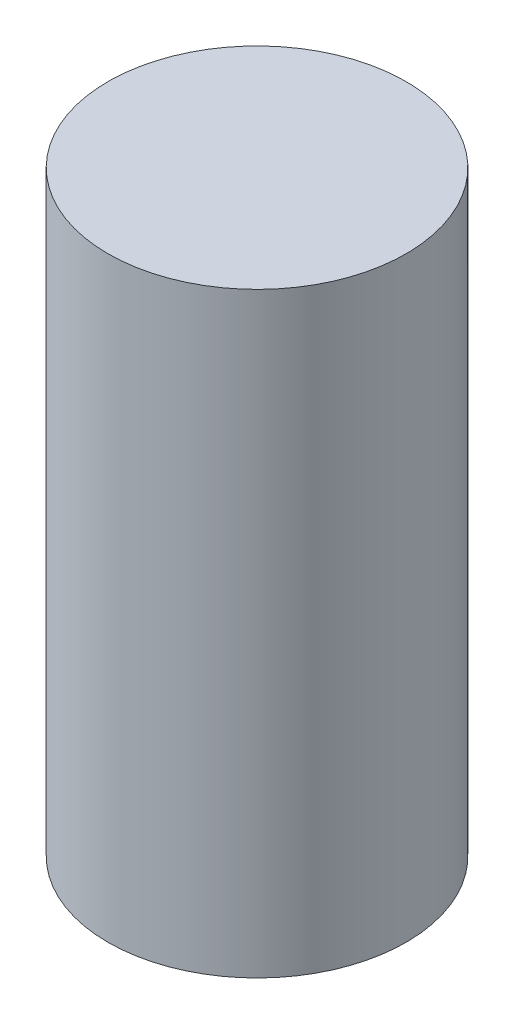
SolidWorks part; units mm, degrees
ref_plane "Front Plane" through (0, 0, 0) normal (0, 0, 1) x (1, 0, 0)
ref_plane "Top Plane" through (0, 0, 0) normal (0, 1, 0) x (1, 0, 0)
ref_plane "Right Plane" through (0, 0, 0) normal (1, 0, 0) x (0, 0, -1)
sketch "Sketch1" plane through (0, 0, 0) normal (0, 1, 0) x (1, 0, 0)
  circle A0 centre (0, 0) radius 7.5
  dimension "D1" = 15
extrude "Boss-Extrude1" add sketch "Sketch1" along normal blind 30
